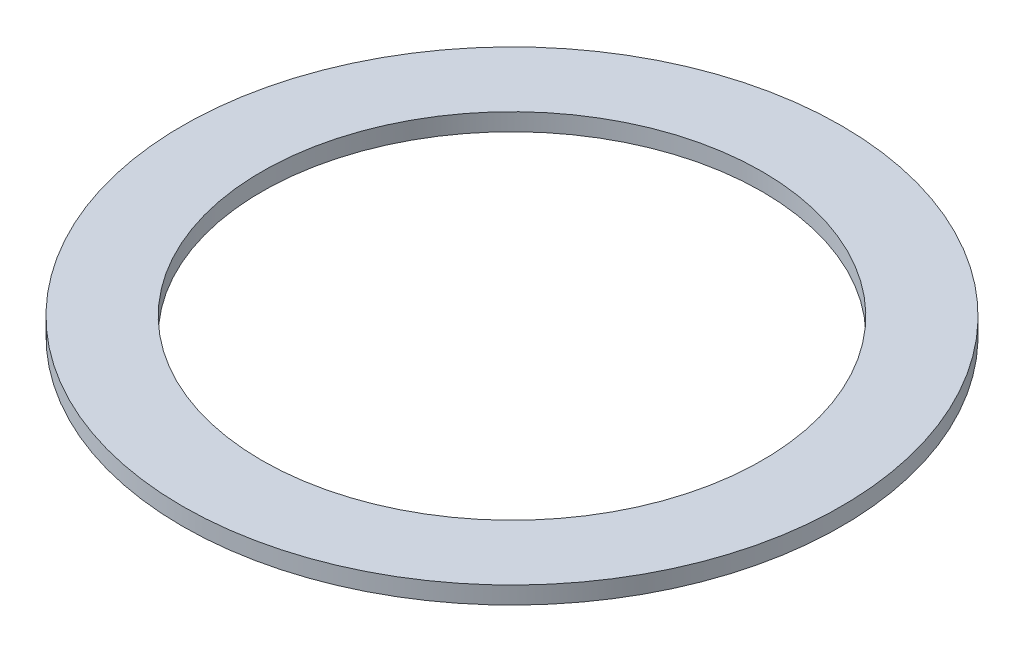
SolidWorks part; units mm, degrees
ref_plane "Front Plane" through (0, 0, 0) normal (0, 0, 1) x (1, 0, 0)
ref_plane "Top Plane" through (0, 0, 0) normal (0, 1, 0) x (1, 0, 0)
ref_plane "Right Plane" through (0, 0, 0) normal (1, 0, 0) x (0, 0, -1)
sketch "Sketch1" plane through (0, 0, 0) normal (0, 1, 0) x (1, 0, 0)
  circle A0 centre (0, 0) radius 38.0746
  circle A1 centre (0, 0) radius 28.9052
  dimension "D1" = 57.8104
  dimension "D2" = 76.1492
extrude "Boss-Extrude1" add sketch "Sketch1" along normal blind 2.0066
